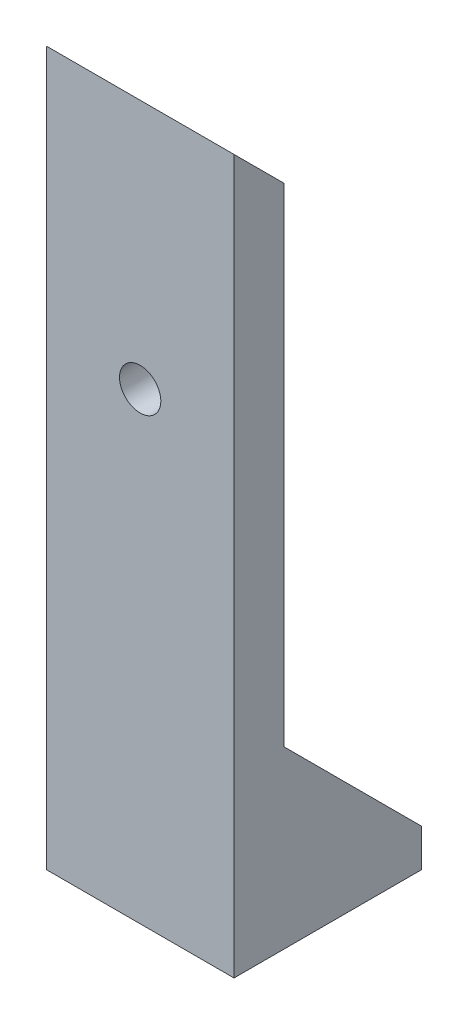
SolidWorks part; units mm, degrees
ref_plane "Front Plane" through (0, 0, 0) normal (0, 0, 1) x (1, 0, 0)
ref_plane "Top Plane" through (0, 0, 0) normal (0, 1, 0) x (1, 0, 0)
ref_plane "Right Plane" through (0, 0, 0) normal (1, 0, 0) x (0, 0, -1)
sketch "Sketch1" plane through (0, 0, 0) normal (0, 1, 0) x (1, 0, 0)
  line L1 (0, 0) -> (15, 0)
  line L2 (0, 0) -> (0, 15)
  line L3 (0, 15) -> (15, 15)
  line L4 (15, 0) -> (15, 15)
  circle A0 centre (7.5, 9) radius 2.65
  dimension "D3" = 5.3
  dimension "D1" = 15
  dimension "D2" = 15
  dimension "D4" = 6
  dimension "D5" = 7.5
extrude "Boss-Extrude1" add sketch "Sketch1" along normal blind 3
sketch "Sketch2" plane through (0, 3, 0) normal (0, 1, 0) x (1, 0, 0)
  line L0 (15, 0) -> (15, 15) construction
  line L1 (0, 0) -> (15, 0)
  line L2 (0, 0) -> (0, 4)
  line L3 (0, 4) -> (15, 4)
  line L4 (15, 0) -> (15, 4)
  dimension "D1" = 4
extrude "Boss-Extrude2" add sketch "Sketch2" along normal blind 54
sketch "Sketch3" plane through (15, 0, 0) normal (1, 0, 0) x (0, 0, -1)
  line L0 (4, 14) -> (15, 3)
  line L1 (4, 57) -> (4, 3) construction
  line L2 (15, 3) -> (4, 3)
  line L3 (4, 3) -> (4, 14)
  dimension "D1" = 45
extrude "Boss-Extrude3" add sketch "Sketch3" against normal blind 3
ref_plane "Plane1" through (7.5, 0, 0) normal (-1, 0, 0) x (0, 0, 1)
mirror "Mirror1" about plane through (7.5, 0, 0) normal (-1, 0, 0) of "Boss-Extrude3"
sketch "Sketch4" plane through (0, 0, -4) normal (0, 0, -1) x (-1, 0, 0)
  line L0 (0, 57) -> (0, 14) construction
  line L2 (-15, 57) -> (0, 57) construction
  circle A0 centre (-7.5, 37) radius 1.65
  dimension "D2" = 3.3
  dimension "D5" = 20
  dimension "D3" = 7.5
extrude "Cut-Extrude1" cut sketch "Sketch4" against normal blind 13
sketch "Sketch5" plane through (15, 0, 0) normal (1, 0, 0) x (0, 0, -1)
  line L0 (0, 57) -> (4, 53)
  line L1 (4, 57) -> (4, 14) construction
  line L2 (0, 57) -> (0, 0) construction
  line L3 (4, 53) -> (4, 57)
  line L4 (4, 57) -> (0, 57)
  dimension "D1" = 45
extrude "Cut-Extrude2" cut sketch "Sketch5" against normal blind 20
